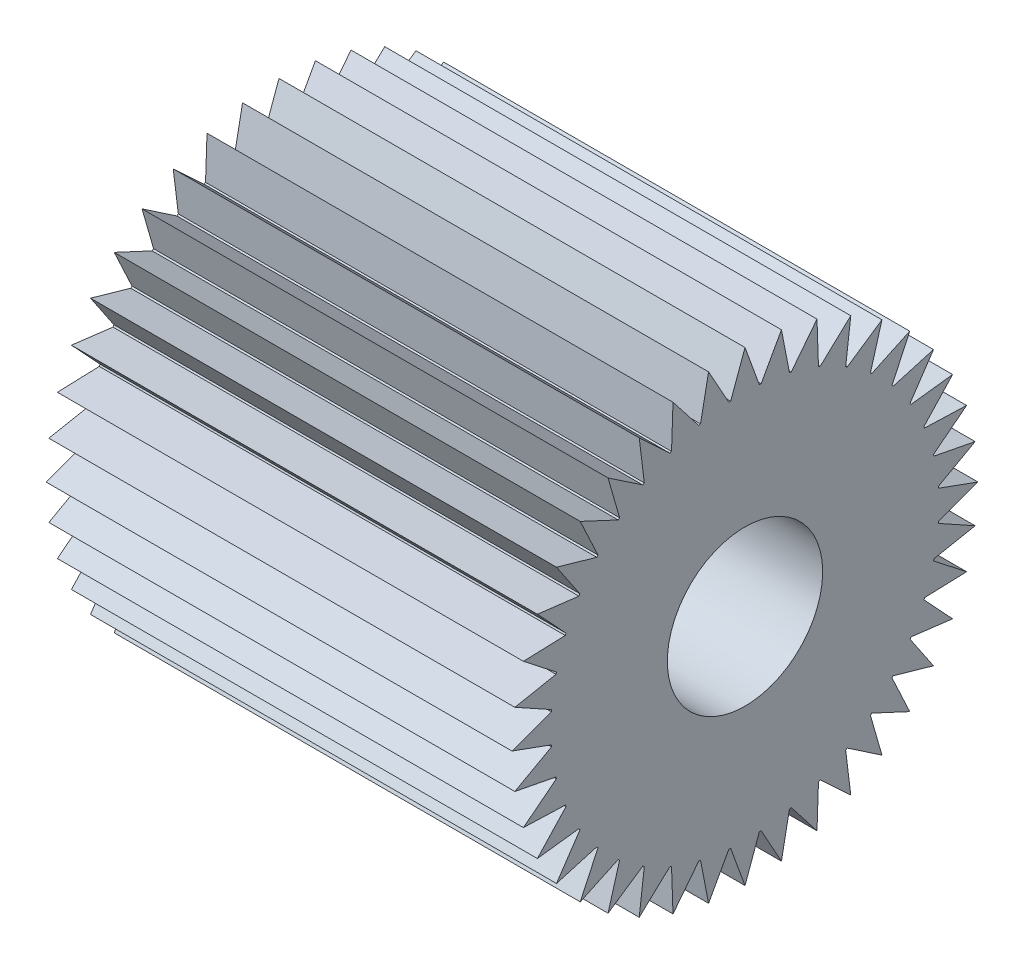
SolidWorks part; units mm, degrees
ref_plane "Front Plane" through (0, 0, 0) normal (0, 0, 1) x (1, 0, 0)
ref_plane "Top Plane" through (0, 0, 0) normal (0, 1, 0) x (1, 0, 0)
ref_plane "Right Plane" through (0, 0, 0) normal (1, 0, 0) x (0, 0, -1)
sketch "Sketch1" plane through (0, 0, 0) normal (1, 0, 0) x (0, 0, -1)
  line L0 (2.3465, 14.8153) -> (2.8611, 12.1682)
  line L1 (0, 15) -> (0.9223, 12.4659)
  line L2 (0, 15) -> (-0.9223, 12.4659)
  line L3 (2.3465, 14.8153) -> (1.0391, 12.4567)
  line L4 (4.6353, 14.2658) -> (4.7294, 11.5708)
  line L5 (4.6353, 14.2658) -> (2.975, 12.1408)
  line L6 (6.8099, 13.3651) -> (6.4812, 10.6885)
  line L7 (6.8099, 13.3651) -> (4.8376, 11.5259)
  line L8 (8.8168, 12.1353) -> (8.0735, 9.543)
  line L9 (8.8168, 12.1353) -> (6.5811, 10.6273)
  line L10 (10.6066, 10.6066) -> (9.4669, 8.1626)
  line L11 (10.6066, 10.6066) -> (8.1626, 9.4669)
  line L12 (12.1353, 8.8168) -> (10.6273, 6.5811)
  line L13 (12.1353, 8.8168) -> (9.543, 8.0735)
  line L14 (13.3651, 6.8099) -> (11.5259, 4.8376)
  line L15 (13.3651, 6.8099) -> (10.6885, 6.4812)
  line L16 (14.2658, 4.6353) -> (12.1408, 2.975)
  line L17 (14.2658, 4.6353) -> (11.5708, 4.7294)
  line L18 (14.8153, 2.3465) -> (12.4567, 1.0391)
  line L19 (14.8153, 2.3465) -> (12.1682, 2.8611)
  line L20 (15, 0) -> (12.4659, -0.9223)
  line L21 (15, 0) -> (12.4659, 0.9223)
  line L22 (14.8153, -2.3465) -> (12.1682, -2.8611)
  line L23 (14.8153, -2.3465) -> (12.4567, -1.0391)
  line L24 (14.2658, -4.6353) -> (11.5708, -4.7294)
  line L25 (14.2658, -4.6353) -> (12.1408, -2.975)
  line L26 (13.3651, -6.8099) -> (10.6885, -6.4812)
  line L27 (13.3651, -6.8099) -> (11.5259, -4.8376)
  line L28 (12.1353, -8.8168) -> (9.543, -8.0735)
  line L29 (12.1353, -8.8168) -> (10.6273, -6.5811)
  line L30 (10.6066, -10.6066) -> (8.1626, -9.4669)
  line L31 (10.6066, -10.6066) -> (9.4669, -8.1626)
  line L32 (8.8168, -12.1353) -> (6.5811, -10.6273)
  line L33 (8.8168, -12.1353) -> (8.0735, -9.543)
  line L34 (6.8099, -13.3651) -> (4.8376, -11.5259)
  line L35 (6.8099, -13.3651) -> (6.4812, -10.6885)
  line L36 (4.6353, -14.2658) -> (2.975, -12.1408)
  line L37 (4.6353, -14.2658) -> (4.7294, -11.5708)
  line L38 (2.3465, -14.8153) -> (1.0391, -12.4567)
  line L39 (2.3465, -14.8153) -> (2.8611, -12.1682)
  line L40 (0, -15) -> (-0.9223, -12.4659)
  line L41 (0, -15) -> (0.9223, -12.4659)
  line L42 (-2.3465, -14.8153) -> (-2.8611, -12.1682)
  line L43 (-2.3465, -14.8153) -> (-1.0391, -12.4567)
  line L44 (-4.6353, -14.2658) -> (-4.7294, -11.5708)
  line L45 (-4.6353, -14.2658) -> (-2.975, -12.1408)
  line L46 (-6.8099, -13.3651) -> (-6.4812, -10.6885)
  line L47 (-6.8099, -13.3651) -> (-4.8376, -11.5259)
  line L48 (-8.8168, -12.1353) -> (-8.0735, -9.543)
  line L49 (-8.8168, -12.1353) -> (-6.5811, -10.6273)
  line L50 (-10.6066, -10.6066) -> (-9.4669, -8.1626)
  line L51 (-10.6066, -10.6066) -> (-8.1626, -9.4669)
  line L52 (-12.1353, -8.8168) -> (-10.6273, -6.5811)
  line L53 (-12.1353, -8.8168) -> (-9.543, -8.0735)
  line L54 (-13.3651, -6.8099) -> (-11.5259, -4.8376)
  line L55 (-13.3651, -6.8099) -> (-10.6885, -6.4812)
  line L56 (-14.2658, -4.6353) -> (-12.1408, -2.975)
  line L57 (-14.2658, -4.6353) -> (-11.5708, -4.7294)
  line L58 (-14.8153, -2.3465) -> (-12.4567, -1.0391)
  line L59 (-14.8153, -2.3465) -> (-12.1682, -2.8611)
  line L60 (-15, 0) -> (-12.4659, 0.9223)
  line L61 (-15, 0) -> (-12.4659, -0.9223)
  line L62 (-14.8153, 2.3465) -> (-12.1682, 2.8611)
  line L63 (-14.8153, 2.3465) -> (-12.4567, 1.0391)
  line L64 (-14.2658, 4.6353) -> (-11.5708, 4.7294)
  line L65 (-14.2658, 4.6353) -> (-12.1408, 2.975)
  line L66 (-13.3651, 6.8099) -> (-10.6885, 6.4812)
  line L67 (-13.3651, 6.8099) -> (-11.5259, 4.8376)
  line L68 (-12.1353, 8.8168) -> (-9.543, 8.0735)
  line L69 (-12.1353, 8.8168) -> (-10.6273, 6.5811)
  line L70 (-10.6066, 10.6066) -> (-8.1626, 9.4669)
  line L71 (-10.6066, 10.6066) -> (-9.4669, 8.1626)
  line L72 (-8.8168, 12.1353) -> (-6.5811, 10.6273)
  line L73 (-8.8168, 12.1353) -> (-8.0735, 9.543)
  line L74 (-6.8099, 13.3651) -> (-4.8376, 11.5259)
  line L75 (-6.8099, 13.3651) -> (-6.4812, 10.6885)
  line L76 (-4.6353, 14.2658) -> (-2.975, 12.1408)
  line L77 (-4.6353, 14.2658) -> (-4.7294, 11.5708)
  line L78 (-2.3465, 14.8153) -> (-1.0391, 12.4567)
  line L79 (-2.3465, 14.8153) -> (-2.8611, 12.1682)
  arc A1 (-0.9223, 12.4659) -> (-1.0391, 12.4567) centre (0, 0) ccw
  arc A2 (-8.0735, 9.543) -> (-8.1626, 9.4669) centre (0, 0) ccw
  arc A3 (-6.4812, 10.6885) -> (-6.5811, 10.6273) centre (0, 0) ccw
  arc A4 (-9.4669, 8.1626) -> (-9.543, 8.0735) centre (0, 0) ccw
  arc A5 (6.5811, 10.6273) -> (6.4812, 10.6885) centre (0, 0) ccw
  arc A6 (4.8376, 11.5259) -> (4.7294, 11.5708) centre (0, 0) ccw
  arc A7 (2.975, 12.1408) -> (2.8611, 12.1682) centre (0, 0) ccw
  arc A8 (-4.7294, 11.5708) -> (-4.8376, 11.5259) centre (0, 0) ccw
  arc A9 (-2.8611, 12.1682) -> (-2.975, 12.1408) centre (0, 0) ccw
  arc A10 (1.0391, 12.4567) -> (0.9223, 12.4659) centre (0, 0) ccw
  arc A11 (-0.9223, 12.4659) -> (-1.0391, 12.4567) centre (0, 0) ccw
  arc A12 (1.0391, 12.4567) -> (0.9223, 12.4659) centre (0, 0) ccw
  arc A13 (-2.8611, 12.1682) -> (-2.975, 12.1408) centre (0, 0) ccw
  arc A14 (2.975, 12.1408) -> (2.8611, 12.1682) centre (0, 0) ccw
  arc A15 (-4.7294, 11.5708) -> (-4.8376, 11.5259) centre (0, 0) ccw
  arc A16 (-10.6273, 6.5811) -> (-10.6885, 6.4812) centre (0, 0) ccw
  arc A17 (-6.4812, 10.6885) -> (-6.5811, 10.6273) centre (0, 0) ccw
  arc A18 (-8.0735, 9.543) -> (-8.1626, 9.4669) centre (0, 0) ccw
  arc A19 (-9.4669, 8.1626) -> (-9.543, 8.0735) centre (0, 0) ccw
  arc A20 (-10.6273, 6.5811) -> (-10.6885, 6.4812) centre (0, 0) ccw
  arc A21 (-11.5259, 4.8376) -> (-11.5708, 4.7294) centre (0, 0) ccw
  arc A22 (-12.4659, -0.9223) -> (-12.4567, -1.0391) centre (0, 0) ccw
  arc A23 (-12.4567, 1.0391) -> (-12.4659, 0.9223) centre (0, 0) ccw
  arc A24 (-12.1408, 2.975) -> (-12.1682, 2.8611) centre (0, 0) ccw
  arc A25 (-12.1682, -2.8611) -> (-12.1408, -2.975) centre (0, 0) ccw
  arc A26 (-11.5708, -4.7294) -> (-11.5259, -4.8376) centre (0, 0) ccw
  arc A27 (-10.6885, -6.4812) -> (-10.6273, -6.5811) centre (0, 0) ccw
  arc A28 (-9.543, -8.0735) -> (-9.4669, -8.1626) centre (0, 0) ccw
  arc A29 (-8.1626, -9.4669) -> (-8.0735, -9.543) centre (0, 0) ccw
  arc A30 (-6.5811, -10.6273) -> (-6.4812, -10.6885) centre (0, 0) ccw
  arc A31 (-4.8376, -11.5259) -> (-4.7294, -11.5708) centre (0, 0) ccw
  arc A32 (-2.975, -12.1408) -> (-2.8611, -12.1682) centre (0, 0) ccw
  arc A33 (-1.0391, -12.4567) -> (-0.9223, -12.4659) centre (0, 0) ccw
  arc A34 (0.9223, -12.4659) -> (1.0391, -12.4567) centre (0, 0) ccw
  arc A35 (2.8611, -12.1682) -> (2.975, -12.1408) centre (0, 0) ccw
  arc A36 (4.7294, -11.5708) -> (4.8376, -11.5259) centre (0, 0) ccw
  arc A37 (6.4812, -10.6885) -> (6.5811, -10.6273) centre (0, 0) ccw
  arc A38 (8.0735, -9.543) -> (8.1626, -9.4669) centre (0, 0) ccw
  arc A39 (9.4669, -8.1626) -> (9.543, -8.0735) centre (0, 0) ccw
  arc A40 (10.6273, -6.5811) -> (10.6885, -6.4812) centre (0, 0) ccw
  arc A41 (11.5259, -4.8376) -> (11.5708, -4.7294) centre (0, 0) ccw
  arc A42 (12.1408, -2.975) -> (12.1682, -2.8611) centre (0, 0) ccw
  arc A43 (12.4567, -1.0391) -> (12.4659, -0.9223) centre (0, 0) ccw
  arc A44 (12.4659, 0.9223) -> (12.4567, 1.0391) centre (0, 0) ccw
  arc A45 (12.1682, 2.8611) -> (12.1408, 2.975) centre (0, 0) ccw
  arc A46 (11.5708, 4.7294) -> (11.5259, 4.8376) centre (0, 0) ccw
  arc A47 (10.6885, 6.4812) -> (10.6273, 6.5811) centre (0, 0) ccw
  arc A48 (8.1626, 9.4669) -> (8.0735, 9.543) centre (0, 0) ccw
  arc A49 (9.543, 8.0735) -> (9.4669, 8.1626) centre (0, 0) ccw
  point P124 (0, 0)
  dimension "D1" = 40
extrude "Boss-Extrude1" add sketch "Sketch1" along normal mid plane 30 contours L13 A49 L10 L11 A48 L8 L9 A5 L6 L7 A6 L4 L5 A7 L0 L3 A10 L1 L2 A1 L78 L79 A9 L76 L77 A8 L74 L75 A3 L72 L73 A2 L70 L71 A4 L68 L69 A16 L66 L67 A21 L64 L65 A24 L62 L63 A23 L60 L61 A22 L58
sketch "Sketch2" plane through (15, 0, 0) normal (1, 0, 0) x (0, 0, -1)
  circle A0 centre (0, 0) radius 5
  dimension "D1" = 10
extrude "Cut-Extrude2" cut sketch "Sketch2" against normal blind 30
